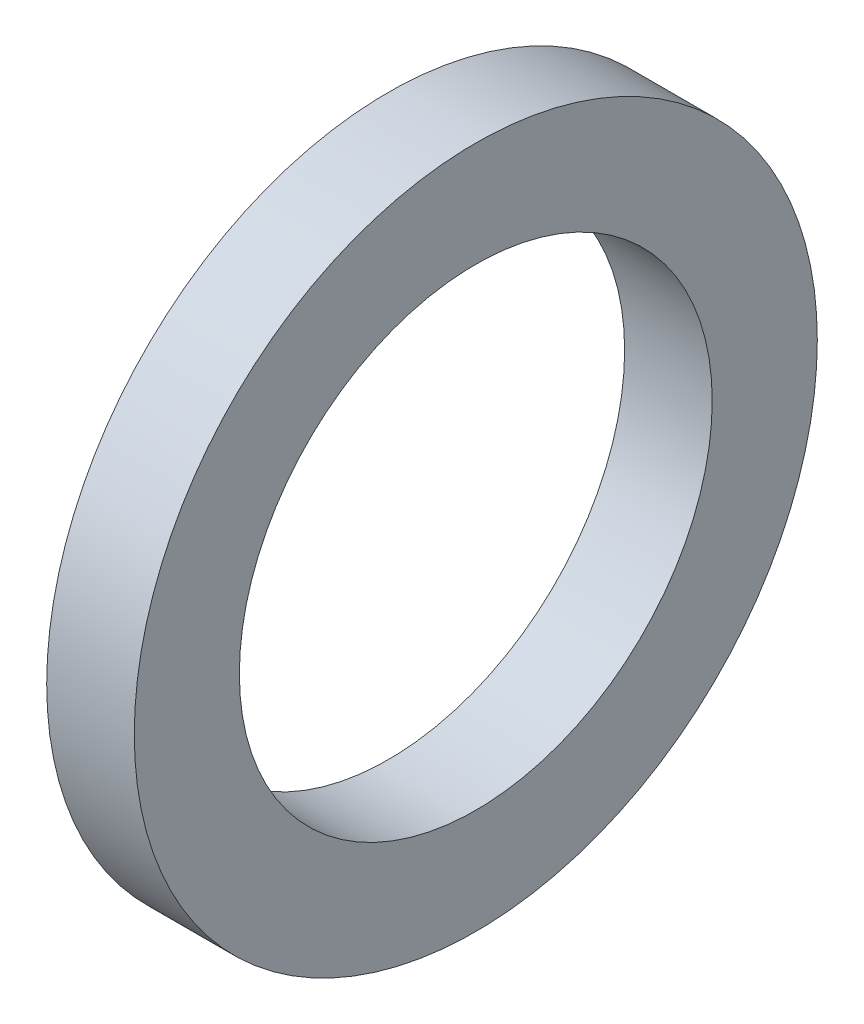
SolidWorks part; units mm, degrees
ref_plane "Plane1" through (0, 0, 0) normal (0, 0, 1) x (1, 0, 0)
ref_plane "Plane2" through (0, 0, 0) normal (0, 1, 0) x (1, 0, 0)
ref_plane "Plane3" through (0, 0, 0) normal (1, 0, 0) x (0, 0, -1)
other "Configuration Table"
sketch "Sketch1" plane through (0, 0, 0) normal (0, 0, 1) x (1, 0, 0)
  line L0 (-34.925, 0) -> (9.525, 0) construction
  line L1 (0, 13.5) -> (0, 19.5)
  line L2 (0, 19.5) -> (-5, 19.5)
  line L3 (-5, 19.5) -> (-5, 13.5)
  line L4 (-5, 13.5) -> (0, 13.5)
  dimension "Thickness" = 5
  dimension "Inside_dia" = 27
  dimension "Outside_dia" = 39
revolve "Base-Revolve" add sketch "Sketch1" angle 360 about L0
